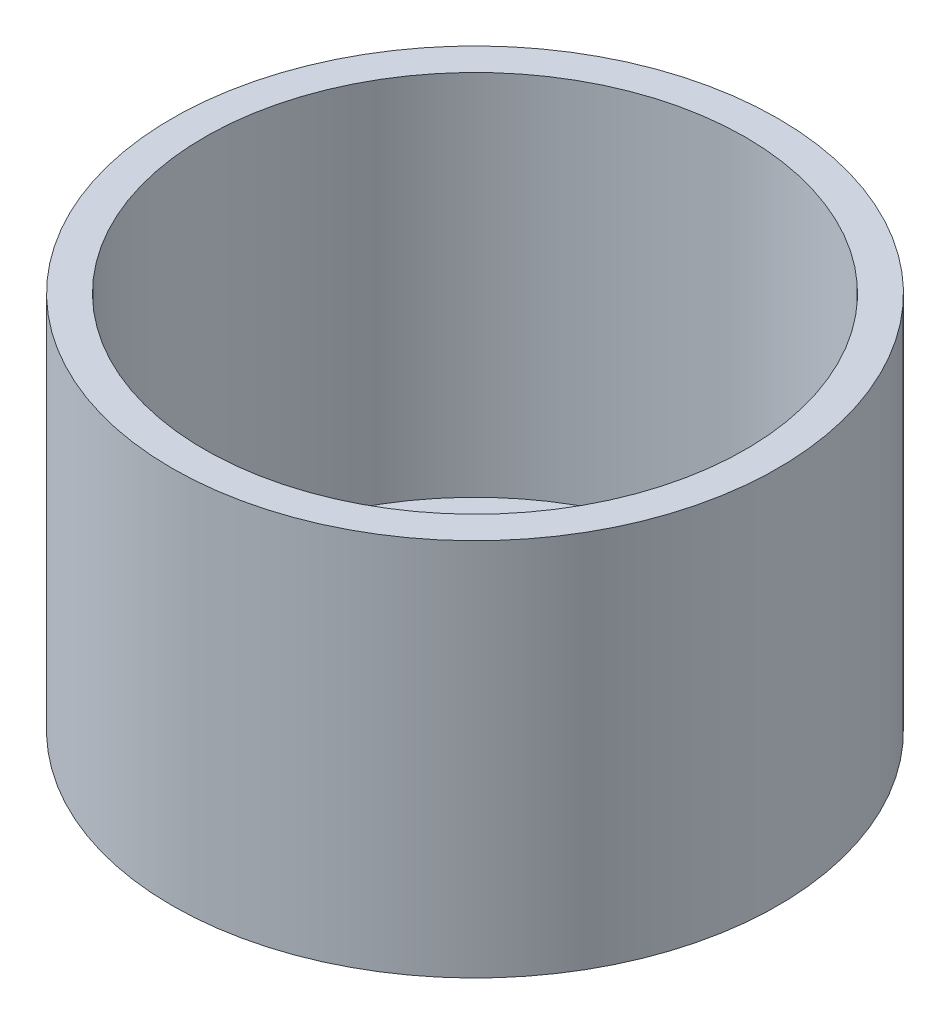
SolidWorks part; units mm, degrees
material "Alumina"
ref_plane "Front Plane" through (0, 0, 0) normal (0, 0, 1) x (1, 0, 0)
ref_plane "Top Plane" through (0, 0, 0) normal (0, 1, 0) x (1, 0, 0)
ref_plane "Right Plane" through (0, 0, 0) normal (1, 0, 0) x (0, 0, -1)
sketch "Sketch1" plane through (0, 0, 0) normal (0, 1, 0) x (1, 0, 0)
  line L1 (-125, -125) -> (125, -125)
  line L2 (-125, -125) -> (-125, 125)
  line L3 (-125, 125) -> (125, 125)
  line L4 (125, -125) -> (125, 125)
  line L5 (-125, -125) -> (125, 125) construction
  line L6 (-125, 125) -> (125, -125) construction
  point P0 (0, 0)
  dimension "D1" = 250
  dimension "D2" = 250
extrude "Boss-Extrude1" add sketch "Sketch1" along normal blind 5
sketch "Sketch8" plane through (0, 5, 0) normal (0, 1, 0) x (1, 0, 0)
  circle A1 centre (0, -95) radius 10 construction
  circle A2 centre (99.779, -1.1471) radius 7.5
  circle A3 centre (0, -95) radius 7.5
  ellipse E1 centre (99.779, -1.1471) end of major axis (89.9596, 0.745) minor radius 9.9963 construction
  dimension "D1" = 15
  dimension "D2" = 15
extrude "Boss-Extrude3" add sketch "Sketch8" along normal blind 5
sketch "Sketch9" plane through (0, 0, 0) normal (1, 0, 0) x (0, 0, -1)
  line L0 (-95, 10) -> (-95, -6.6364) construction
  line L1 (-87.5, 10) -> (-102.5, 10) construction
  line L2 (-95, 15) -> (-95, 5)
  arc A0 (-95, 15) -> (-95, 5) centre (-95, 10) ccw
  dimension "D1" = 10
revolve "Cut-Revolve3" cut sketch "Sketch9" angle 360 about L0
ref_plane "Plane1" through (0, 0, 1.05) normal (0, 0, 1) x (1, 0, 0)
sketch "Sketch10" plane through (0, 0, 1.05) normal (0, 0, 1) x (1, 0, 0)
  line L0 (99.779, 15) -> (99.779, 5)
  line L1 (107.279, 10) -> (92.279, 10) construction
  arc A0 (99.779, 15) -> (99.779, 5) centre (99.779, 10) ccw
  dimension "D1" = 10
revolve "Cut-Revolve4" cut sketch "Sketch10" angle 360 about L0
fillet "Fillet6" radius 2 2 edges at (99.779, 5, -6.3529) (0, 5, 87.5)
fillet "Fillet7" radius 0.5 2 edges at (99.779, 10, 8.6471) (0, 10, 102.5)
sketch "Sketch11" plane through (0, 5, 0) normal (0, 1, 0) x (1, 0, 0)
  line L4 (125, -125) -> (125, 125)
  line L5 (125, 125) -> (-125, 125)
  line L6 (-125, 125) -> (-125, -125)
  line L7 (-125, -125) -> (125, -125)
  line L8 (125, -125) -> (125, 125)
  line L9 (125, 125) -> (-125, 125)
  line L10 (-125, 125) -> (-125, -125)
  line L11 (-125, -125) -> (125, -125)
  circle A0 centre (-47.523, 40.2081) radius 2.5 construction
  circle A1 centre (-19.2407, 30.2025) radius 2.5 construction
  circle A2 centre (-9.2351, 58.4849) radius 2.5 construction
  circle A3 centre (-37.5174, 68.4904) radius 2.5 construction
  circle A4 centre (-47.523, 40.2081) radius 2.5
  circle A5 centre (-19.2407, 30.2025) radius 2.5
  circle A6 centre (-9.2351, 58.4849) radius 2.5
  circle A7 centre (-37.5174, 68.4904) radius 2.5
  dimension "D1" = 0
extrude "Cut-Extrude4" cut sketch "Sketch11" against normal blind 10 contours A5 | A7 | A4 | A6
sketch "Sketch12" plane through (0, 0, 0) normal (0, -1, 0) x (-1, 0, 0)
  circle A0 centre (0, 0) radius 125
extrude "Cut-Extrude5" cut sketch "Sketch12" against normal blind 10 flip side to cut
sketch "Sketch13" plane through (0, 0, 0) normal (0, -1, 0) x (1, 0, 0)
  circle A0 centre (0, 0) radius 125
  circle A1 centre (0, 0) radius 140
extrude "Boss-Extrude4" add sketch "Sketch13" against normal blind 175
sketch "Sketch15" plane through (0, 175, 0) normal (0, 1, 0) x (1, 0, 0)
  circle A0 centre (0, 0) radius 140
  circle A1 centre (0, 0) radius 100
  dimension "D1" = 280
